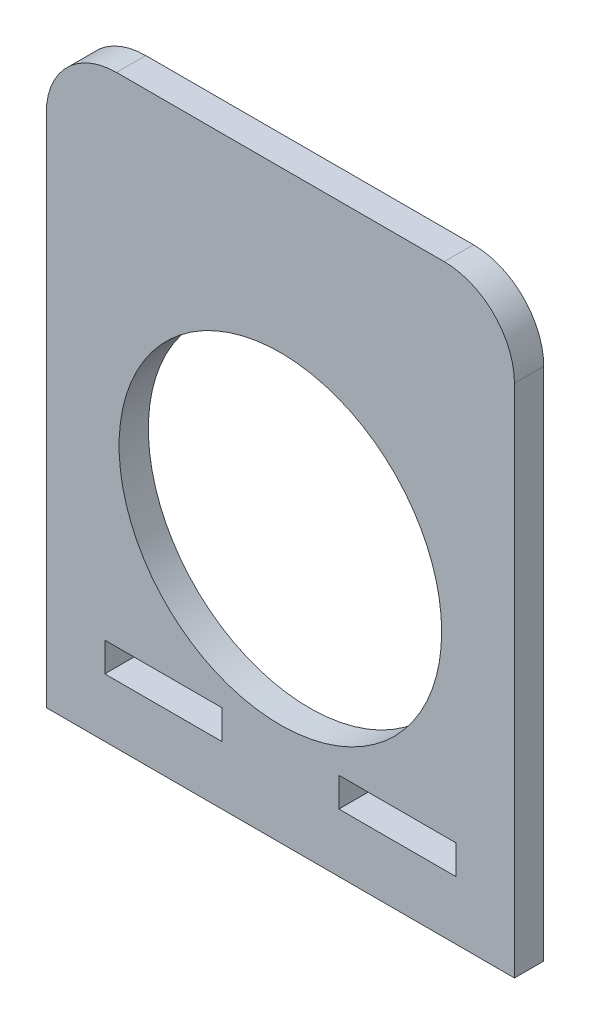
SolidWorks part; units mm, degrees
ref_plane "Front Plane" through (0, 0, 0) normal (0, 0, 1) x (1, 0, 0)
ref_plane "Top Plane" through (0, 0, 0) normal (0, 1, 0) x (1, 0, 0)
ref_plane "Right Plane" through (0, 0, 0) normal (1, 0, 0) x (0, 0, -1)
sketch "Sketch1" plane through (0, 0, 0) normal (0, 0, 1) x (1, 0, 0)
  line L2 (0, 0) -> (50.8, 0)
  line L3 (50.8, 0) -> (50.8, 55.88)
  line L4 (43.18, 63.5) -> (7.62, 63.5)
  line L5 (0, 55.88) -> (0, 0)
  line L8 (25.4, 28.575) -> (25.4, 0) construction
  line L9 (19.05, 7.9375) -> (25.4, 7.9375) construction
  line L10 (6.35, 6.35) -> (19.05, 6.35)
  line L11 (6.35, 6.35) -> (6.35, 9.525)
  line L12 (6.35, 9.525) -> (19.05, 9.525)
  line L13 (19.05, 6.35) -> (19.05, 9.525)
  line L14 (31.75, 6.35) -> (44.45, 6.35)
  line L15 (31.75, 6.35) -> (31.75, 9.525)
  line L17 (44.45, 6.35) -> (44.45, 9.525)
  line L18 (31.75, 7.9375) -> (25.4, 7.9375) construction
  line L19 (31.75, 9.525) -> (44.45, 9.525)
  circle A0 centre (25.4, 28.575) radius 17.5
  arc A1 (50.8, 55.88) -> (43.18, 63.5) centre (43.18, 55.88) ccw
  arc A2 (7.62, 63.5) -> (0, 55.88) centre (7.62, 55.88) ccw
  point P15 (50.8, 63.5)
  dimension "D2" = 35
  dimension "D6" = 7.62
  dimension "D1" = 6.35
  dimension "D3" = 3.175
  dimension "D4" = 12.7
  dimension "D5" = 19.05
  dimension "D7" = 12.7
  dimension "D8" = 50.8
  dimension "D9" = 63.5
extrude "Boss-Extrude1" add sketch "Sketch1" along normal blind 3.175
